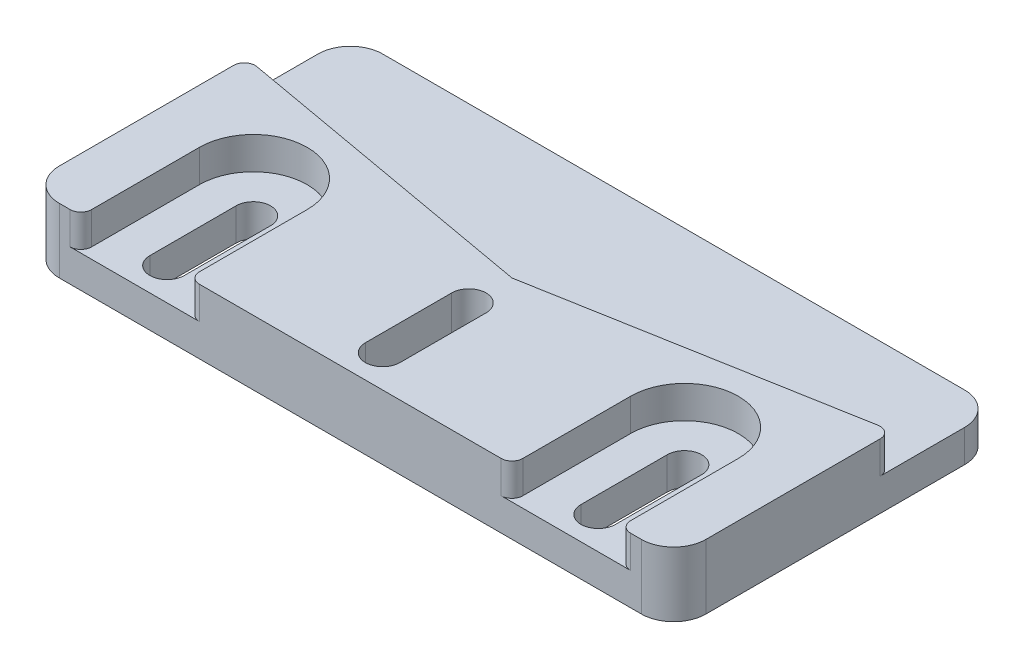
SolidWorks part; units mm, degrees
ref_plane "Front Plane" through (0, 0, 0) normal (0, 0, 1) x (1, 0, 0)
ref_plane "Top Plane" through (0, 0, 0) normal (0, 1, 0) x (1, 0, 0)
ref_plane "Right Plane" through (0, 0, 0) normal (1, 0, 0) x (0, 0, -1)
sketch "Sketch1" plane through (0, 0, 0) normal (0, 1, 0) x (1, 0, 0)
  line L1 (-30, -7.5) -> (30, -7.5)
  line L2 (-30, -7.5) -> (-30, 7.5)
  line L3 (-30, 7.5) -> (30, 7.5)
  line L4 (30, -7.5) -> (30, 7.5)
  line L5 (-30, -7.5) -> (30, 7.5) construction
  line L6 (-30, 7.5) -> (30, -7.5) construction
  point P0 (0, 0)
  dimension "D1" = 15
  dimension "D2" = 60
sketch "Sketch2" plane through (0, 0, 0) normal (0, 1, 0) x (1, 0, 0)
  line L0 (-30, 7.5) -> (30, 7.5) construction
  line L1 (-30, -7.5) -> (30, -7.5)
  line L2 (-30, -7.5) -> (-30, 11.6647)
  line L4 (30, -7.5) -> (30, 11.6647)
  arc A0 (-28.6548, 12.6032) -> (28.6548, 12.6032) centre (0, 90.5) ccw
  arc A1 (28.6548, 12.6032) -> (30, 11.6647) centre (29, 11.6647) cw
  arc A2 (-28.6548, 12.6032) -> (-30, 11.6647) centre (-29, 11.6647) ccw
  dimension "D1" = 83
  dimension "D2" = 1
extrude "Boss-Extrude1" add sketch "Sketch2" along normal blind 3
sketch "Sketch4" plane through (0, 0, 0) normal (0, -1, 0) x (1, 0, 0)
  line L1 (-30, 7.5) -> (30, 7.5)
  line L2 (-30, 7.5) -> (-30, -22.5)
  line L3 (-30, -22.5) -> (30, -22.5)
  line L4 (30, 7.5) -> (30, -22.5)
  dimension "D1" = 30
extrude "Boss-Extrude2" add sketch "Sketch4" along normal blind 3
fillet "Fillet1" radius 3 4 edges at (30, -1.5, -22.5) (30, 0, 7.5) (-30, 0, 7.5) (-30, -1.5, -22.5)
sketch "Sketch5" plane through (0, 3, 0) normal (0, 1, 0) x (1, 0, 0)
  line L0 (0, 3.5) -> (0, -4.5) construction
  line L1 (0, -54.6431) -> (0, 54.6431) construction
  line L2 (1.6, 3.5) -> (1.6, -4.5)
  line L3 (-1.6, 3.5) -> (-1.6, -4.5)
  line L4 (-30, -7.5) -> (30, -7.5) construction
  line L5 (20, 3.5) -> (20, -4.5) construction
  line L6 (21.6, 3.5) -> (21.6, -4.5)
  line L7 (18.4, 3.5) -> (18.4, -4.5)
  line L8 (0, 24.3668) -> (0, -20.2781) construction
  line L9 (-20, 3.5) -> (-20, -4.5) construction
  line L10 (-21.6, 3.5) -> (-21.6, -4.5)
  line L11 (-18.4, 3.5) -> (-18.4, -4.5)
  arc A0 (1.6, 3.5) -> (-1.6, 3.5) centre (0, 3.5) ccw
  arc A1 (-1.6, -4.5) -> (1.6, -4.5) centre (0, -4.5) ccw
  arc A2 (21.6, 3.5) -> (18.4, 3.5) centre (20, 3.5) ccw
  arc A3 (18.4, -4.5) -> (21.6, -4.5) centre (20, -4.5) ccw
  arc A4 (-21.6, 3.5) -> (-18.4, 3.5) centre (-20, 3.5) cw
  arc A5 (-18.4, -4.5) -> (-21.6, -4.5) centre (-20, -4.5) cw
  point P5 (0, -0.5)
  point P16 (20, -0.5)
  point P23 (-20, -0.5)
  dimension "D1" = 3.2
  dimension "D2" = 3
  dimension "D3" = 8
  dimension "D4" = 2
extrude "Cut-Extrude1" cut sketch "Sketch5" against normal through all
sketch "Sketch6" plane through (0, 3, 0) normal (0, 1, 0) x (1, 0, 0)
  line L0 (0, 7.5) -> (-28.8241, 12.6491)
  line L1 (-30, 7.5) -> (30, 7.5) construction
  line L5 (-27, -7.5) -> (27, -7.5)
  line L6 (30, -4.5) -> (30, 11.6647)
  line L7 (-30, 11.6647) -> (-30, -4.5)
  line L8 (-27, -7.5) -> (27, -7.5)
  line L9 (30, -4.5) -> (30, 11.6647)
  line L10 (-30, 11.6647) -> (-30, -4.5)
  line L11 (-18.4, -4.5) -> (-18.4, 3.5)
  line L12 (-21.6, 3.5) -> (-21.6, -4.5)
  line L13 (-18.4, -4.5) -> (-18.4, 3.5)
  line L14 (-21.6, 3.5) -> (-21.6, -4.5)
  line L15 (0, 7.5) -> (28.8241, 12.6491)
  line L16 (1.6, -4.5) -> (1.6, 3.5)
  line L17 (-1.6, 3.5) -> (-1.6, -4.5)
  line L18 (1.6, -4.5) -> (1.6, 3.5)
  line L19 (-1.6, 3.5) -> (-1.6, -4.5)
  line L21 (21.6, -4.5) -> (21.6, 3.5)
  line L22 (18.4, 3.5) -> (18.4, -4.5)
  line L23 (21.6, -4.5) -> (21.6, 3.5)
  line L24 (18.4, 3.5) -> (18.4, -4.5)
  arc A0 (-28.6548, 12.6032) -> (-30, 11.6647) centre (-29, 11.6647) ccw construction
  arc A1 (-28.6548, 12.6032) -> (-30, 11.6647) centre (-29, 11.6647) ccw construction
  arc A4 (-18.4, 3.5) -> (-21.6, 3.5) centre (-20, 3.5) ccw
  arc A5 (-21.6, -4.5) -> (-18.4, -4.5) centre (-20, -4.5) ccw
  arc A6 (-18.4, 3.5) -> (-21.6, 3.5) centre (-20, 3.5) ccw
  arc A7 (27, -7.5) -> (30, -4.5) centre (27, -4.5) ccw
  arc A8 (30, 11.6647) -> (28.6548, 12.6032) centre (29, 11.6647) ccw
  arc A9 (-28.6548, 12.6032) -> (28.6548, 12.6032) centre (0, 90.5) ccw
  arc A10 (-28.6548, 12.6032) -> (-30, 11.6647) centre (-29, 11.6647) ccw
  arc A11 (-30, -4.5) -> (-27, -7.5) centre (-27, -4.5) ccw
  arc A12 (27, -7.5) -> (30, -4.5) centre (27, -4.5) ccw
  arc A13 (30, 11.6647) -> (28.8241, 12.6491) centre (29, 11.6647) ccw
  arc A15 (-28.8241, 12.6491) -> (-30, 11.6647) centre (-29, 11.6647) ccw
  arc A16 (-30, -4.5) -> (-27, -7.5) centre (-27, -4.5) ccw
  arc A17 (-21.6, -4.5) -> (-18.4, -4.5) centre (-20, -4.5) ccw
  arc A18 (1.6, 3.5) -> (-1.6, 3.5) centre (0, 3.5) ccw
  arc A19 (-1.6, -4.5) -> (1.6, -4.5) centre (0, -4.5) ccw
  arc A20 (1.6, 3.5) -> (-1.6, 3.5) centre (0, 3.5) ccw
  arc A21 (-1.6, -4.5) -> (1.6, -4.5) centre (0, -4.5) ccw
  arc A22 (21.6, 3.5) -> (18.4, 3.5) centre (20, 3.5) ccw
  arc A23 (18.4, -4.5) -> (21.6, -4.5) centre (20, -4.5) ccw
  arc A24 (21.6, 3.5) -> (18.4, 3.5) centre (20, 3.5) ccw
  arc A25 (18.4, -4.5) -> (21.6, -4.5) centre (20, -4.5) ccw
  dimension "D1" = 0
  dimension "D2" = 0
  dimension "D3" = 0
  dimension "D4" = 0
extrude "Boss-Extrude3" add sketch "Sketch6" against normal up to surface (3 mm away) up to face at (0.1682, 0, -16.0844)
sketch "Sketch7" plane through (0, 3, 0) normal (0, 1, 0) x (1, 0, 0)
  line L0 (-20, 3.5) -> (-20, -15.7) construction
  line L1 (-15, 3.5) -> (-15, -15.7)
  line L2 (-25, 3.5) -> (-25, -15.7)
  line L8 (20, 3.5) -> (20, -15.7) construction
  line L9 (25, 3.5) -> (25, -15.7)
  line L10 (15, 3.5) -> (15, -15.7)
  arc A0 (-15, 3.5) -> (-25, 3.5) centre (-20, 3.5) ccw
  arc A1 (-25, -15.7) -> (-15, -15.7) centre (-20, -15.7) ccw
  arc A2 (-18.4, 3.5) -> (-21.6, 3.5) centre (-20, 3.5) ccw construction
  arc A3 (-21.6, -4.5) -> (-18.4, -4.5) centre (-20, -4.5) ccw construction
  arc A6 (25, 3.5) -> (15, 3.5) centre (20, 3.5) ccw
  arc A7 (15, -15.7) -> (25, -15.7) centre (20, -15.7) ccw
  point P2 (-20, -6.1)
  point P26 (20, -6.1)
  dimension "D1" = 10
extrude "Cut-Extrude2" cut sketch "Sketch7" against normal blind 3
fillet "Fillet2" radius 1 4 edges at (25, 1.5, 7.5) (15, 1.5, 7.5) (-15, 1.5, 7.5) (-25, 1.5, 7.5)
